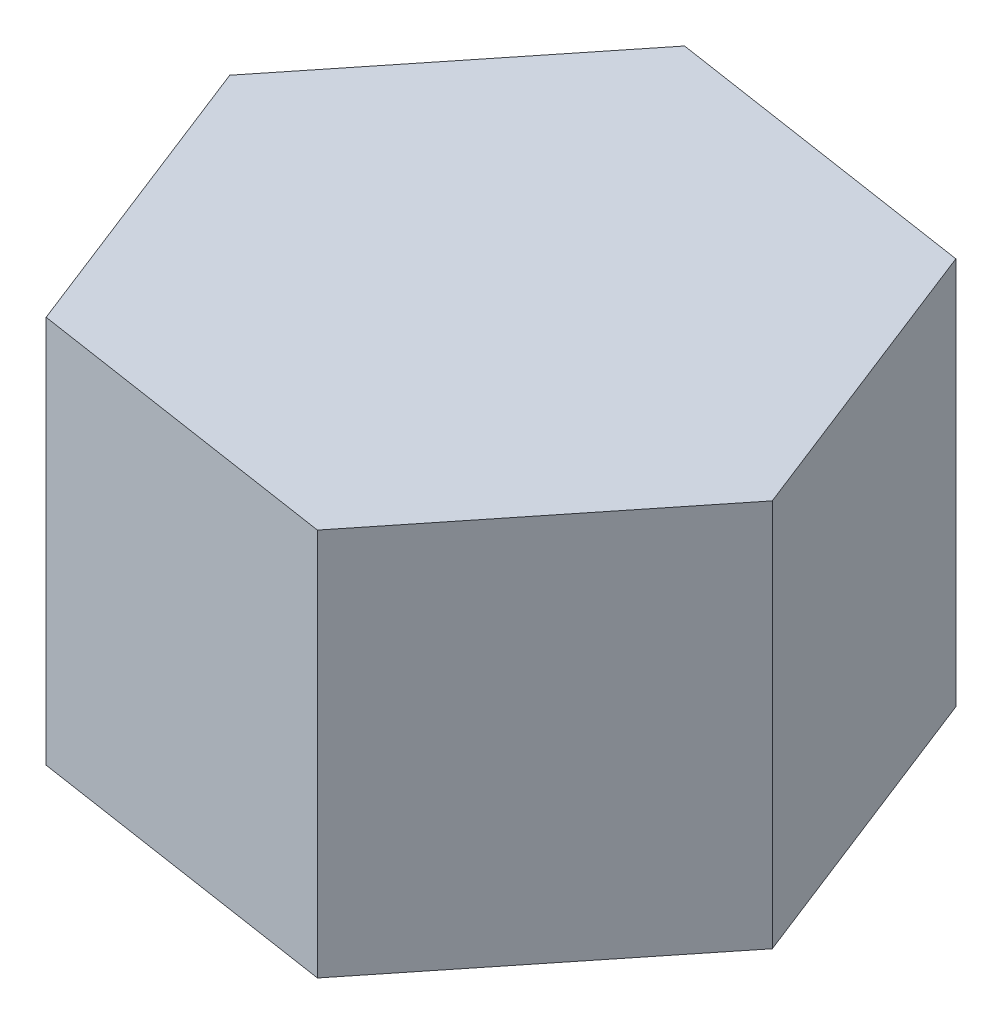
SolidWorks part; units mm, degrees
ref_plane "前视基准面" through (0, 0, 0) normal (0, 0, 1) x (1, 0, 0)
ref_plane "上视基准面" through (0, 0, 0) normal (0, 1, 0) x (1, 0, 0)
ref_plane "右视基准面" through (0, 0, 0) normal (1, 0, 0) x (0, 0, -1)
sketch "草图1" plane through (0, 0, 0) normal (0, 1, 0) x (1, 0, 0)
  line L1 (3.6473, 4.5609) -> (-2.1262, 5.4391)
  line L2 (-2.1262, 5.4391) -> (-5.7735, 0.8782)
  line L3 (-5.7735, 0.8782) -> (-3.6473, -4.5609)
  line L4 (-3.6473, -4.5609) -> (2.1262, -5.4391)
  line L5 (2.1262, -5.4391) -> (5.7735, -0.8782)
  line L6 (5.7735, -0.8782) -> (3.6473, 4.5609)
  circle A0 centre (0, 0) radius 5.0575 construction
  point P1 (0.7606, 5)
  dimension "D1" = 5
extrude "凸台-拉伸1" add sketch "草图1" along normal blind 7
sketch "草图2" plane through (0, 0, 0) normal (0, -1, 0) x (-1, 0, 0)
  line L0 (-4.2, 1.3) -> (-4.2, -1.1)
  line L1 (4.2, 1.3) -> (-4.2, 1.3)
  line L2 (4.2, 1.3) -> (4.2, -1.1)
  line L7 (-4.2, -1.1) -> (4.2, -1.1)
  point P1 (0, 1.3)
  point P2 (0, -1.1)
  dimension "D1" = 2.4
extrude "切除-拉伸1" cut sketch "草图2" against normal blind 5
